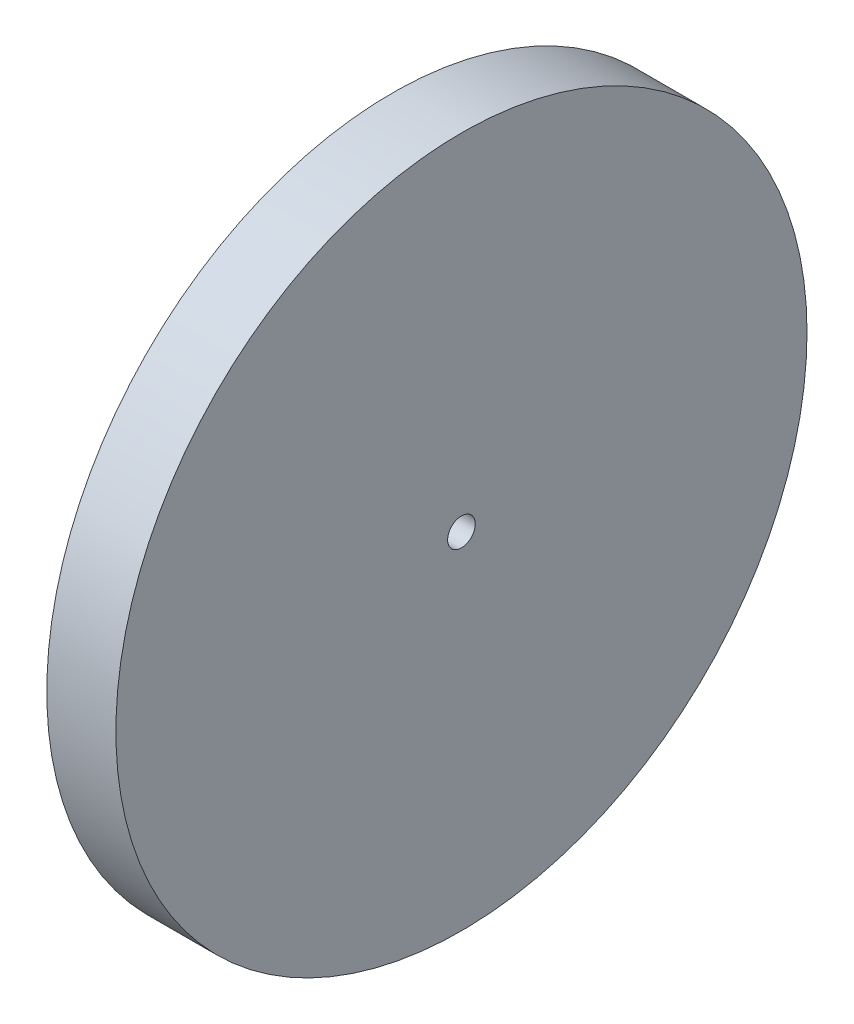
SolidWorks part; units mm, degrees
ref_plane "Front Plane" through (0, 0, 0) normal (0, 0, 1) x (1, 0, 0)
ref_plane "Top Plane" through (0, 0, 0) normal (0, 1, 0) x (1, 0, 0)
ref_plane "Right Plane" through (0, 0, 0) normal (1, 0, 0) x (0, 0, -1)
sketch "Sketch1" plane through (0, 0, 0) normal (1, 0, 0) x (0, 0, -1)
  circle A0 centre (0, 0) radius 100
  dimension "D1" = 200
extrude "Boss-Extrude1" add sketch "Sketch1" along normal blind 20
sketch "Sketch2" plane through (0, 0, 0) normal (-1, 0, 0) x (0, 0, 1)
  circle A0 centre (0, 0) radius 70
  dimension "D1" = 140
extrude "Boss-Extrude2" add sketch "Sketch2" along normal blind 20
sketch "Sketch3" plane through (-20, 0, 0) normal (-1, 0, 0) x (0, 0, 1)
  circle A0 centre (0, 0) radius 4
  dimension "D1" = 8
extrude "Cut-Extrude1" cut sketch "Sketch3" against normal up to next
